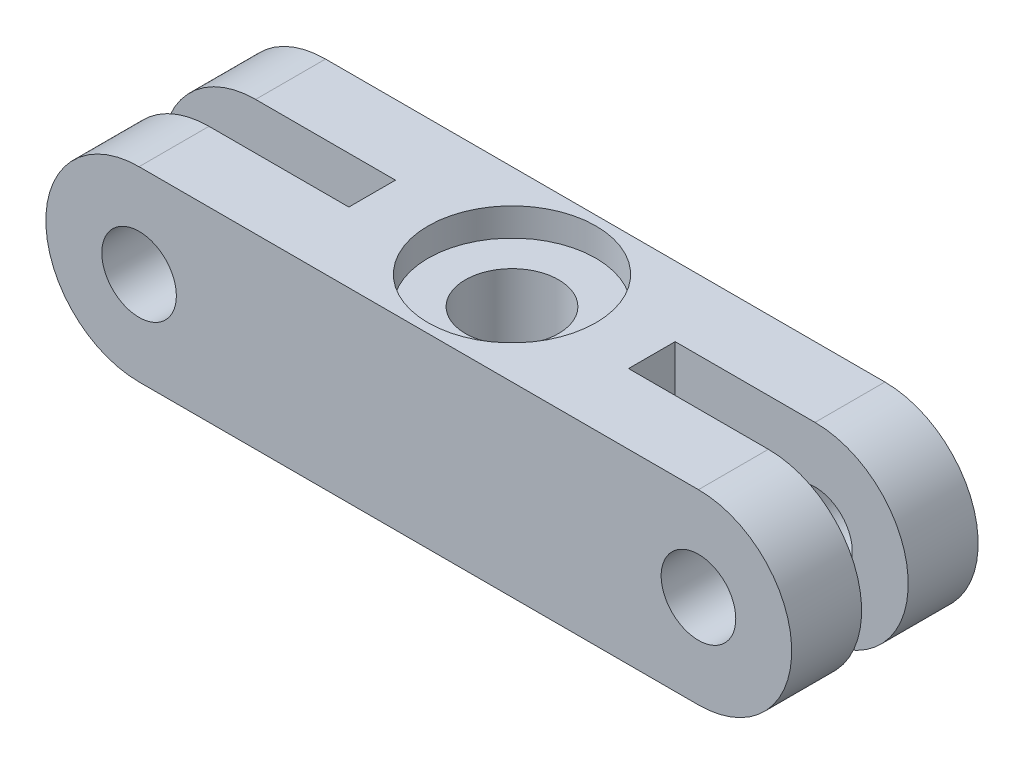
SolidWorks part; units mm, degrees
ref_plane "Front Plane" through (0, 0, 0) normal (0, 0, 1) x (1, 0, 0)
ref_plane "Top Plane" through (0, 0, 0) normal (0, 1, 0) x (1, 0, 0)
ref_plane "Right Plane" through (0, 0, 0) normal (1, 0, 0) x (0, 0, -1)
sketch "Sketch1" plane through (0, 0, 0) normal (0, 0, 1) x (1, 0, 0)
  line L0 (0, 0) -> (60, 0) construction
  line L1 (0, 10) -> (60, 10)
  line L2 (0, -10) -> (60, -10)
  arc A0 (0, 10) -> (0, -10) centre (0, 0) ccw
  arc A1 (60, -10) -> (60, 10) centre (60, 0) ccw
  circle A2 centre (0, 0) radius 4
  circle A3 centre (60, 0) radius 4
  point P3 (30, 0)
  dimension "D1" = 10
  dimension "D3" = 8
  dimension "D2" = 60
extrude "Boss-Extrude1" add sketch "Sketch1" along normal mid plane 20
sketch "Sketch2" plane through (0, 0, 0) normal (0, 1, 0) x (1, 0, 0)
  line L0 (70, -10) -> (70, 10) construction
  line L1 (45, -2.5) -> (70, -2.5)
  line L2 (45, -2.5) -> (45, 2.5)
  line L3 (45, 2.5) -> (70, 2.5)
  line L4 (70, -2.5) -> (70, 2.5)
  line L5 (45, -2.5) -> (70, 2.5) construction
  line L6 (45, 2.5) -> (70, -2.5) construction
  line L7 (30, 10) -> (30, -10) construction
  line L8 (60, 10) -> (0, 10) construction
  line L9 (60, -10) -> (0, -10) construction
  line L10 (15, 2.5) -> (-10, -2.5) construction
  line L11 (15, -2.5) -> (-10, 2.5) construction
  line L12 (-10, -2.5) -> (-10, 2.5)
  line L13 (15, 2.5) -> (-10, 2.5)
  line L14 (15, -2.5) -> (15, 2.5)
  line L15 (15, -2.5) -> (-10, -2.5)
  point P0 (57.5, 0)
  point P18 (2.5, 0)
  point P19 (30, 0)
  dimension "D1" = 25
  dimension "D2" = 5
extrude "Cut-Extrude2" cut sketch "Sketch2" against normal through all both and the other way through all
hole_wizard "Hole1" positions "Sketch6" profile "Sketch5" legacy end condition up to next
sketch "Sketch6" plane through (0, 10, 0) normal (0, 1, 0) x (1, 0, 0)
  line L0 (30, 10) -> (30, -10) construction
  point P0 (30, 0)
sketch "Sketch5" plane through (30, 10, 0) normal (1, 0, 0) x (0, 0, 1)
  line L0 (0, 0) -> (0, 20)
  line L1 (0, 20) -> (5, 20)
  line L2 (5, 20) -> (5, 3)
  line L3 (5, 3) -> (9, 3)
  line L4 (9, 3) -> (9, 0)
  line L5 (9, 0) -> (0, 0)
  line L6 (0, 110) -> (0, -10) construction
  dimension "Diameter" = 10
  dimension "Depth" = 20
  dimension "C-Bore Diameter" = 18
  dimension "C-Bore Depth" = 3
